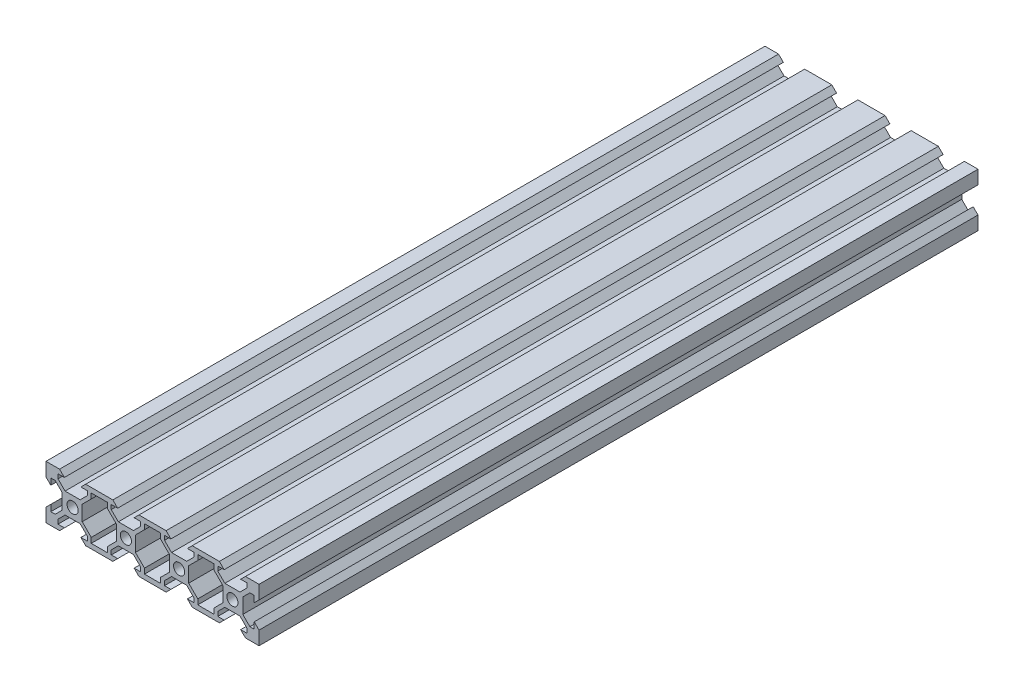
SolidWorks part; units mm, degrees
ref_plane "Plan de face" through (0, 0, 0) normal (0, 0, 1) x (1, 0, 0)
ref_plane "Plan de dessus" through (0, 0, 0) normal (0, 1, 0) x (1, 0, 0)
ref_plane "Plan de droite" through (0, 0, 0) normal (1, 0, 0) x (0, 0, -1)
sketch "Esquisse1" plane through (0, 0, 0) normal (0, 0, 1) x (1, 0, 0)
  line L45 (-65.6277, 8.2661) -> (14.3723, 8.2661)
  line L46 (-65.6277, 8.2661) -> (-65.6277, -11.7339)
  line L47 (-65.6277, -11.7339) -> (14.3723, -11.7339)
  line L48 (14.3723, 8.2661) -> (14.3723, -11.7339)
  dimension "D1" = 80
  dimension "D2" = 20
extrude "Boss.-Extru.1" add sketch "Esquisse1" along normal blind 270
sketch "Esquisse2" plane through (0, 0, 0) normal (0, 0, -1) x (-1, 0, 0)
  line L0 (-14.3723, -11.7339) -> (-14.3723, 8.2661) construction
  line L2 (50.7277, 8.2661) -> (60.5277, 8.2661)
  line L3 (-14.3723, 8.2661) -> (65.6277, 8.2661) construction
  line L4 (60.5277, 8.2661) -> (58.7277, 6.4661)
  line L5 (58.7277, 6.4661) -> (61.1277, 6.4661)
  line L6 (61.1277, 6.4661) -> (61.1277, 4.8261)
  line L7 (61.1277, 4.8261) -> (58.4677, 2.1661)
  line L8 (58.4677, 2.1661) -> (52.7877, 2.1661)
  line L9 (52.7877, 2.1661) -> (50.1277, 4.8261)
  line L10 (50.1277, 4.8261) -> (50.1277, 6.4661)
  line L11 (50.1277, 6.4661) -> (52.5277, 6.4661)
  line L12 (52.5277, 6.4661) -> (50.7277, 8.2661)
  line L43 (65.6277, 8.2661) -> (65.6277, -11.7339) construction
  line L44 (65.6277, 3.1661) -> (65.6277, -6.6339)
  line L45 (65.6277, -6.6339) -> (63.8277, -4.8339)
  line L46 (63.8277, -4.8339) -> (63.8277, -7.2339)
  line L47 (63.8277, -7.2339) -> (62.1877, -7.2339)
  line L48 (62.1877, -7.2339) -> (59.5277, -4.5739)
  line L49 (59.5277, -4.5739) -> (59.5277, 1.1061)
  line L50 (59.5277, 1.1061) -> (62.1877, 3.7661)
  line L51 (62.1877, 3.7661) -> (63.8277, 3.7661)
  line L52 (63.8277, 3.7661) -> (63.8277, 1.3661)
  line L53 (63.8277, 1.3661) -> (65.6277, 3.1661)
  line L54 (60.5277, -11.7339) -> (50.7277, -11.7339)
  line L55 (50.7277, -11.7339) -> (52.5277, -9.9339)
  line L56 (52.5277, -9.9339) -> (50.1277, -9.9339)
  line L57 (50.1277, -9.9339) -> (50.1277, -8.2939)
  line L58 (50.1277, -8.2939) -> (52.7877, -5.6339)
  line L59 (52.7877, -5.6339) -> (58.4677, -5.6339)
  line L60 (58.4677, -5.6339) -> (61.1277, -8.2939)
  line L61 (61.1277, -8.2939) -> (61.1277, -9.9339)
  line L62 (61.1277, -9.9339) -> (58.7277, -9.9339)
  line L63 (58.7277, -9.9339) -> (60.5277, -11.7339)
  line L64 (55.6277, -1.7339) -> (58.4677, 2.1661) construction
  line L65 (55.6277, -1.7339) -> (59.5277, -4.5739) construction
  line L66 (30.7277, 8.2661) -> (40.5277, 8.2661)
  line L67 (40.5277, 8.2661) -> (38.7277, 6.4661)
  line L68 (38.7277, 6.4661) -> (41.1277, 6.4661)
  line L69 (41.1277, 6.4661) -> (41.1277, 4.8261)
  line L70 (41.1277, 4.8261) -> (38.4677, 2.1661)
  line L71 (38.4677, 2.1661) -> (32.7877, 2.1661)
  line L72 (32.7877, 2.1661) -> (30.1277, 4.8261)
  line L73 (30.1277, 4.8261) -> (30.1277, 6.4661)
  line L74 (30.1277, 6.4661) -> (32.5277, 6.4661)
  line L75 (32.5277, 6.4661) -> (30.7277, 8.2661)
  line L76 (40.5277, -11.7339) -> (30.7277, -11.7339)
  line L77 (30.7277, -11.7339) -> (32.5277, -9.9339)
  line L78 (32.5277, -9.9339) -> (30.1277, -9.9339)
  line L79 (30.1277, -9.9339) -> (30.1277, -8.2939)
  line L80 (30.1277, -8.2939) -> (32.7877, -5.6339)
  line L81 (32.7877, -5.6339) -> (38.4677, -5.6339)
  line L82 (38.4677, -5.6339) -> (41.1277, -8.2939)
  line L83 (41.1277, -8.2939) -> (41.1277, -9.9339)
  line L84 (41.1277, -9.9339) -> (38.7277, -9.9339)
  line L85 (38.7277, -9.9339) -> (40.5277, -11.7339)
  line L86 (35.6277, -1.7339) -> (38.4677, 2.1661) construction
  line L87 (10.7277, 8.2661) -> (20.5277, 8.2661)
  line L88 (20.5277, 8.2661) -> (18.7277, 6.4661)
  line L89 (18.7277, 6.4661) -> (21.1277, 6.4661)
  line L90 (21.1277, 6.4661) -> (21.1277, 4.8261)
  line L91 (21.1277, 4.8261) -> (18.4677, 2.1661)
  line L92 (18.4677, 2.1661) -> (12.7877, 2.1661)
  line L93 (12.7877, 2.1661) -> (10.1277, 4.8261)
  line L94 (10.1277, 4.8261) -> (10.1277, 6.4661)
  line L95 (10.1277, 6.4661) -> (12.5277, 6.4661)
  line L96 (12.5277, 6.4661) -> (10.7277, 8.2661)
  line L97 (20.5277, -11.7339) -> (10.7277, -11.7339)
  line L98 (10.7277, -11.7339) -> (12.5277, -9.9339)
  line L99 (12.5277, -9.9339) -> (10.1277, -9.9339)
  line L100 (10.1277, -9.9339) -> (10.1277, -8.2939)
  line L101 (10.1277, -8.2939) -> (12.7877, -5.6339)
  line L102 (12.7877, -5.6339) -> (18.4677, -5.6339)
  line L103 (18.4677, -5.6339) -> (21.1277, -8.2939)
  line L104 (21.1277, -8.2939) -> (21.1277, -9.9339)
  line L105 (21.1277, -9.9339) -> (18.7277, -9.9339)
  line L106 (18.7277, -9.9339) -> (20.5277, -11.7339)
  line L107 (15.6277, -1.7339) -> (18.4677, 2.1661) construction
  line L108 (-9.2723, 8.2661) -> (0.5277, 8.2661)
  line L109 (0.5277, 8.2661) -> (-1.2723, 6.4661)
  line L110 (-1.2723, 6.4661) -> (1.1277, 6.4661)
  line L111 (1.1277, 6.4661) -> (1.1277, 4.8261)
  line L112 (1.1277, 4.8261) -> (-1.5323, 2.1661)
  line L113 (-1.5323, 2.1661) -> (-7.2123, 2.1661)
  line L114 (-7.2123, 2.1661) -> (-9.8723, 4.8261)
  line L115 (-9.8723, 4.8261) -> (-9.8723, 6.4661)
  line L116 (-9.8723, 6.4661) -> (-7.4723, 6.4661)
  line L117 (-7.4723, 6.4661) -> (-9.2723, 8.2661)
  line L118 (0.5277, -11.7339) -> (-9.2723, -11.7339)
  line L119 (-9.2723, -11.7339) -> (-7.4723, -9.9339)
  line L120 (-7.4723, -9.9339) -> (-9.8723, -9.9339)
  line L121 (-9.8723, -9.9339) -> (-9.8723, -8.2939)
  line L122 (-9.8723, -8.2939) -> (-7.2123, -5.6339)
  line L123 (-7.2123, -5.6339) -> (-1.5323, -5.6339)
  line L124 (-1.5323, -5.6339) -> (1.1277, -8.2939)
  line L125 (1.1277, -8.2939) -> (1.1277, -9.9339)
  line L126 (1.1277, -9.9339) -> (-1.2723, -9.9339)
  line L127 (-1.2723, -9.9339) -> (0.5277, -11.7339)
  line L128 (-4.3723, -1.7339) -> (-1.5323, 2.1661) construction
  line L129 (-14.3723, -6.6339) -> (-14.3723, 3.1661)
  line L130 (-14.3723, 3.1661) -> (-12.5723, 1.3661)
  line L131 (-12.5723, 1.3661) -> (-12.5723, 3.7661)
  line L132 (-12.5723, 3.7661) -> (-10.9323, 3.7661)
  line L133 (-10.9323, 3.7661) -> (-8.2723, 1.1061)
  line L134 (-8.2723, 1.1061) -> (-8.2723, -4.5739)
  line L135 (-8.2723, -4.5739) -> (-10.9323, -7.2339)
  line L136 (-10.9323, -7.2339) -> (-12.5723, -7.2339)
  line L137 (-12.5723, -7.2339) -> (-12.5723, -4.8339)
  line L138 (-12.5723, -4.8339) -> (-14.3723, -6.6339)
  line L139 (-4.3723, -1.7339) -> (-1.5323, 2.1661) construction
  line L140 (-4.3723, -1.7339) -> (-8.2723, 1.1061) construction
  circle A0 centre (55.6277, -1.7339) radius 2.1
  circle A1 centre (35.6277, -1.7339) radius 2.1
  circle A2 centre (15.6277, -1.7339) radius 2.1
  circle A3 centre (-4.3723, -1.7339) radius 2.1
  point P5 (-14.3723, -1.7339)
  point P17 (55.6277, 2.1661)
  point P54 (10.6277, 13.2661)
  dimension "D1" = 4.2
  dimension "D2" = 135
  dimension "D3" = 1.64
  dimension "D4" = 5.68
  dimension "D5" = 1.8
  dimension "D6" = 6.2
  dimension "D7" = 11
  dimension "D8" = 10
  dimension "D10" = 90
  dimension "D13" = 90
  dimension "D11" = 4
  dimension "D9" = 3
  dimension "D12" = 2
extrude "Enlèv. mat.-Extru.1" cut sketch "Esquisse2" against normal up to next
sketch "Esquisse3" plane through (0, 0, 0) normal (0, 0, -1) x (-1, 0, 0)
  line L0 (2.6183, 6.4661) -> (8.6372, 6.4661)
  line L1 (8.6372, 6.4661) -> (8.6372, 4.5061)
  line L2 (8.6372, 4.5061) -> (12.0372, 1.1061)
  line L3 (12.0372, 1.1061) -> (12.0372, -4.5739)
  line L4 (12.0372, -4.5739) -> (8.6372, -7.9739)
  line L5 (8.6372, -7.9739) -> (8.6372, -9.9339)
  line L6 (8.6372, -9.9339) -> (2.6183, -9.9339)
  line L7 (2.6183, -9.9339) -> (2.6183, -7.9739)
  line L8 (2.6183, -7.9739) -> (-0.7817, -4.5739)
  line L9 (-0.7817, -4.5739) -> (-0.7817, 1.1061)
  line L10 (-0.7817, 1.1061) -> (2.6183, 4.5061)
  line L11 (2.6183, 4.5061) -> (2.6183, 6.4661)
  line L12 (0.5277, 8.2661) -> (10.7277, 8.2661) construction
  line L13 (-1.2723, -9.9339) -> (1.1277, -9.9339) construction
  line L14 (1.1277, 6.4661) -> (-1.2723, 6.4661) construction
  line L15 (22.6183, 6.4661) -> (28.6372, 6.4661)
  line L16 (28.6372, 6.4661) -> (28.6372, 4.5061)
  line L17 (28.6372, 4.5061) -> (32.0372, 1.1061)
  line L18 (32.0372, 1.1061) -> (32.0372, -4.5739)
  line L19 (32.0372, -4.5739) -> (28.6372, -7.9739)
  line L20 (28.6372, -7.9739) -> (28.6372, -9.9339)
  line L21 (28.6372, -9.9339) -> (22.6183, -9.9339)
  line L22 (22.6183, -9.9339) -> (22.6183, -7.9739)
  line L23 (22.6183, -7.9739) -> (19.2183, -4.5739)
  line L24 (19.2183, -4.5739) -> (19.2183, 1.1061)
  line L25 (19.2183, 1.1061) -> (22.6183, 4.5061)
  line L26 (22.6183, 4.5061) -> (22.6183, 6.4661)
  line L27 (42.6183, 6.4661) -> (48.6372, 6.4661)
  line L28 (48.6372, 6.4661) -> (48.6372, 4.5061)
  line L29 (48.6372, 4.5061) -> (52.0372, 1.1061)
  line L30 (52.0372, 1.1061) -> (52.0372, -4.5739)
  line L31 (52.0372, -4.5739) -> (48.6372, -7.9739)
  line L32 (48.6372, -7.9739) -> (48.6372, -9.9339)
  line L33 (48.6372, -9.9339) -> (42.6183, -9.9339)
  line L34 (42.6183, -9.9339) -> (42.6183, -7.9739)
  line L35 (42.6183, -7.9739) -> (39.2183, -4.5739)
  line L36 (39.2183, -4.5739) -> (39.2183, 1.1061)
  line L37 (39.2183, 1.1061) -> (42.6183, 4.5061)
  line L38 (42.6183, 4.5061) -> (42.6183, 6.4661)
  circle A0 centre (-4.3723, -1.7339) radius 2.1 construction
  circle A1 centre (-4.3723, -1.7339) radius 2.1 construction
  point P13 (5.6277, 6.4661)
  point P16 (5.6277, 8.2661)
  point P28 (-0.7817, -1.7339)
  point P29 (12.0372, -1.7339)
  dimension "D1" = 5.68
  dimension "D2" = 1.96
  dimension "D3" = 3
extrude "Enlèv. mat.-Extru.2" cut sketch "Esquisse3" against normal up to next
